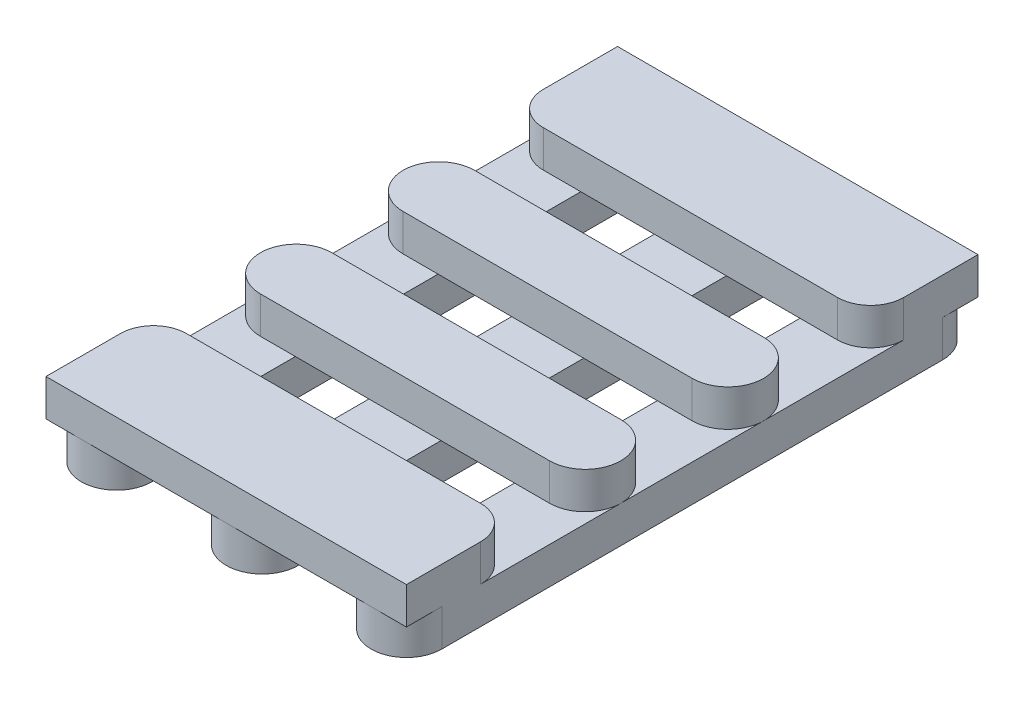
SolidWorks part; units mm, degrees
ref_plane "Front Plane" through (0, 0, 0) normal (0, 0, 1) x (1, 0, 0)
ref_plane "Top Plane" through (0, 0, 0) normal (0, 1, 0) x (1, 0, 0)
ref_plane "Right Plane" through (0, 0, 0) normal (1, 0, 0) x (0, 0, -1)
sketch "Sketch1" plane through (0, 0, 0) normal (0, 1, 0) x (1, 0, 0)
  line L1 (-23.3656, -38.85) -> (16.6344, -38.85)
  line L2 (-27.8656, -34.35) -> (-27.8656, 34.35)
  line L3 (-23.3656, 38.85) -> (16.6344, 38.85)
  line L4 (21.1344, -34.35) -> (21.1344, 34.35)
  arc A0 (-27.8656, -34.35) -> (-23.3656, -38.85) centre (-23.3656, -34.35) ccw
  arc A1 (21.1344, -34.35) -> (16.6344, -38.85) centre (16.6344, -34.35) cw
  arc A2 (-23.3656, 38.85) -> (-27.8656, 34.35) centre (-23.3656, 34.35) ccw
  arc A3 (21.1344, 34.35) -> (16.6344, 38.85) centre (16.6344, 34.35) ccw
  point P0 (0, 0)
  point P14 (21.1344, -38.85)
  point P17 (-27.8656, 38.85)
  point P20 (21.1344, 38.85)
  dimension "D5" = 4.5
  dimension "D1" = 77.7
  dimension "D2" = 49
extrude "Boss-Extrude1" add sketch "Sketch1" along normal blind 10 contours L2 A0 L1 A1 L4 A3 L3 A2
sketch "Sketch2" plane through (0, 10, 0) normal (0, 1, 0) x (1, 0, 0)
  line L0 (-23.3656, 24.25) -> (16.6344, 24.25)
  line L1 (-27.8656, 14.55) -> (21.1344, 14.55)
  line L2 (-27.8656, 4.85) -> (21.1344, 4.85)
  line L3 (-27.8656, -4.85) -> (21.1344, -4.85)
  line L4 (-27.8656, 34.35) -> (-27.8656, -34.35)
  line L5 (-23.3656, -38.85) -> (16.6344, -38.85)
  line L6 (21.1344, -34.35) -> (21.1344, 34.35)
  line L7 (16.6344, 38.85) -> (-23.3656, 38.85)
  line L8 (-27.8656, 34.35) -> (-27.8656, 28.75)
  line L9 (-23.3656, -38.85) -> (16.6344, -38.85)
  line L10 (21.1344, 28.75) -> (21.1344, 34.35)
  line L11 (16.6344, 38.85) -> (-23.3656, 38.85)
  line L12 (-27.8656, -14.55) -> (21.1344, -14.55)
  line L13 (21.1344, 14.55) -> (21.1344, 4.85)
  line L14 (-23.3656, -24.25) -> (16.6344, -24.25)
  line L15 (-27.8656, 14.55) -> (-27.8656, 4.85)
  line L16 (-27.8656, -4.85) -> (-27.8656, -14.55)
  line L17 (21.1344, -4.85) -> (21.1344, -14.55)
  line L18 (-27.8656, -28.75) -> (-27.8656, -33.2156)
  line L19 (-27.8656, -34.35) -> (-27.8656, 34.35) construction
  line L20 (21.1344, -28.75) -> (21.1344, -31.0612)
  line L21 (21.1344, -34.35) -> (21.1344, 34.35) construction
  arc A0 (21.1344, 28.75) -> (16.6344, 24.25) centre (16.6344, 28.75) cw
  arc A1 (-27.8656, 28.75) -> (-23.3656, 24.25) centre (-23.3656, 28.75) ccw
  circle A2 centre (16.2844, 9.7) radius 4.85
  circle A3 centre (16.2844, -9.7) radius 4.85
  arc A4 (-23.3656, 38.85) -> (-27.8656, 34.35) centre (-23.3656, 34.35) ccw
  arc A5 (-27.8656, -34.35) -> (-23.3656, -38.85) centre (-23.3656, -34.35) ccw
  arc A6 (16.6344, -38.85) -> (21.1344, -34.35) centre (16.6344, -34.35) ccw
  arc A7 (21.1344, 34.35) -> (16.6344, 38.85) centre (16.6344, 34.35) ccw
  arc A8 (-23.3656, 38.85) -> (-27.8656, 34.35) centre (-23.3656, 34.35) ccw
  arc A9 (-27.8656, -34.35) -> (-23.3656, -38.85) centre (-23.3656, -34.35) ccw
  arc A10 (16.6344, -38.85) -> (21.1344, -34.35) centre (16.6344, -34.35) ccw
  arc A11 (21.1344, 34.35) -> (16.6344, 38.85) centre (16.6344, 34.35) ccw
  circle A12 centre (-23.0156, 9.7) radius 4.85
  circle A13 centre (-23.0156, -9.7) radius 4.85
  arc A14 (16.6344, -24.25) -> (21.1344, -28.75) centre (16.6344, -28.75) cw
  arc A15 (-23.3656, -24.25) -> (-27.8656, -28.75) centre (-23.3656, -28.75) ccw
  point P28 (16.2844, 14.55)
  point P30 (17.6053, -4.85)
  point P31 (17.6053, -14.55)
  point P32 (-24.5992, -14.55)
  point P33 (-24.5992, -4.85)
  point P34 (-24.5992, 4.85)
  point P35 (-24.5992, 14.55)
  point P48 (21.1344, -24.25)
  point P54 (-27.8656, -24.25)
  line M16 (-27.8656, 34.35) -> (-27.8656, -34.35)
  line M20 (21.1344, -34.35) -> (21.1344, 34.35)
  dimension "D8" = 4.5
  dimension "D9" = 4.5
  dimension "D12" = 9.7
  dimension "D13" = 4.85
  dimension "D15" = 9.7
  dimension "D16" = 9.7
  dimension "D21" = 9.7
  dimension "D22" = 4.5
  dimension "D2" = 14.6
  dimension "D3" = 9.7
  dimension "D4" = 9.7
  dimension "D5" = 14.6
  dimension "D6" = 9.7
  dimension "D7" = 9.7
  dimension "D10" = 4.85
  dimension "D11" = 4.85
  dimension "D14" = 4.85
  dimension "D17" = 4.85
  dimension "D18" = 4.85
  dimension "D19" = 4.85
  dimension "D20" = 4.85
  dimension "D1" = 0
extrude "Cut-Extrude3" cut sketch "Sketch2" against normal blind 5 contours A15 L14 A14 L12 M20 M16 | A13 L16 L12 | A3 L12 M20 | A3 L17 L3 | A13 L3 M16 | L3 L2 M16 M20 | A12 L15 L2 | A2 L2 M20 | A12 L1 M16 | A1 L1 A0 L0 M16 M20 | A2 L13 L1
sketch "Sketch4" plane through (0, 0, 0) normal (0, -1, 0) x (1, 0, 0)
  line L0 (-18.1156, 38.85) -> (-18.1156, -38.85)
  line L1 (-8.2906, 38.85) -> (-8.2906, -38.85)
  line L2 (1.5594, 38.85) -> (1.5594, -38.85)
  line L3 (11.3844, 38.85) -> (11.3844, -38.85)
  line L4 (-23.3656, -38.85) -> (16.6344, -38.85)
  line L5 (21.1344, -34.35) -> (21.1344, 34.35)
  line L6 (16.6344, 38.85) -> (-23.3656, 38.85)
  line L7 (-27.8656, 34.35) -> (-27.8656, -34.35)
  line L8 (-23.3656, -38.85) -> (16.6344, -38.85)
  line L9 (21.1344, -34.35) -> (21.1344, 34.35)
  line L10 (16.6344, 38.85) -> (-23.3656, 38.85)
  line L11 (-27.8656, 34.35) -> (-27.8656, -34.35)
  line L12 (-27.8656, 34.1766) -> (-27.8656, 38.85)
  line L13 (-27.8656, 38.85) -> (-23.3656, 38.85)
  line L14 (-23.3656, 38.85) -> (-23.3656, 35.6156)
  line L15 (-23.3656, 35.6156) -> (-27.8656, 34.1766)
  line L16 (-27.8656, -34.35) -> (-27.8656, -38.85)
  line L17 (-27.8656, -38.85) -> (-23.3656, -38.85)
  line L18 (-23.1567, -35.5858) -> (-27.8656, -34.35)
  line L19 (-23.3656, -38.85) -> (-23.1567, -35.5858)
  line L20 (16.6344, -38.85) -> (21.1344, -38.85)
  line L21 (21.1344, -38.85) -> (21.1344, -34.35)
  line L22 (16.6344, -38.85) -> (16.6344, -34.745)
  line L23 (16.6344, -34.745) -> (21.1344, -34.35)
  line L24 (16.6344, 38.85) -> (21.1344, 38.85)
  line L25 (21.1344, 38.85) -> (21.1344, 34.35)
  line L26 (21.1344, 34.35) -> (17.4288, 36.8474)
  line L27 (17.4288, 36.8474) -> (16.6344, 38.85)
  arc A4 (-27.8656, -34.35) -> (-23.3656, -38.85) centre (-23.3656, -34.35) ccw
  arc A5 (16.6344, -38.85) -> (21.1344, -34.35) centre (16.6344, -34.35) ccw
  arc A6 (21.1344, 34.35) -> (16.6344, 38.85) centre (16.6344, 34.35) ccw
  arc A7 (-23.3656, 38.85) -> (-27.8656, 34.35) centre (-23.3656, 34.35) ccw
  arc A8 (-27.8656, -34.35) -> (-23.3656, -38.85) centre (-23.3656, -34.35) ccw
  arc A9 (16.6344, -38.85) -> (21.1344, -34.35) centre (16.6344, -34.35) ccw
  arc A10 (21.1344, 34.35) -> (16.6344, 38.85) centre (16.6344, 34.35) ccw
  arc A11 (-23.3656, 38.85) -> (-27.8656, 34.35) centre (-23.3656, 34.35) ccw
  arc M21 (-27.8656, -34.35) -> (-23.3656, -38.85) centre (-23.3656, -34.35) ccw
  arc M23 (16.6344, -38.85) -> (21.1344, -34.35) centre (16.6344, -34.35) ccw
  arc M25 (21.1344, 34.35) -> (16.6344, 38.85) centre (16.6344, 34.35) ccw
  arc M27 (-23.3656, 38.85) -> (-27.8656, 34.35) centre (-23.3656, 34.35) ccw
  line M28 (-27.8656, 34.35) -> (-27.8656, -34.35)
  dimension "D3" = 9.75
  dimension "D2" = 9.75
  dimension "D4" = 9.85
  dimension "D5" = 9.825
  dimension "D1" = 0
extrude "Boss-Extrude6" add sketch "Sketch4" along normal blind 5 and the other way blind 10 contours L13 L12 M27 | L15 L14 M27 M28 | L27 L26 M25 | L25 L24 M25 | L23 L22 M23 | L20 L21 M23 | L19 L18 M21 | L16 L17 M21
sketch "Sketch5" plane through (21.1344, 0, 0) normal (1, 0, 0) x (0, 0, -1)
  line L1 (-38.85, 0) -> (41.5848, 0)
  line L2 (-38.85, 0) -> (-38.85, -11.4679)
  line L3 (-38.85, -11.4679) -> (41.5848, -11.4679)
  line L4 (41.5848, 0) -> (41.5848, -11.4679)
  line L14 (9.7, 5) -> (-9.7, 5)
  line L15 (-9.7, 5) -> (-28.75, 5)
  line L16 (-28.75, 5) -> (-28.75, 10)
  line L17 (-28.75, 10) -> (-38.85, 10)
  line L18 (-38.85, 10) -> (-38.85, -5)
  line L19 (-38.85, -5) -> (-34.35, -5)
  line L20 (-34.35, -5) -> (-34.35, 0)
  line L21 (-34.35, 0) -> (34.35, 0)
  line L22 (34.35, 0) -> (34.35, -5)
  line L23 (34.35, -5) -> (38.85, -5)
  line L24 (38.85, -5) -> (38.85, 10)
  line L25 (38.85, 10) -> (28.75, 10)
  line L26 (28.75, 10) -> (28.75, 5)
  line L27 (28.75, 5) -> (9.7, 5)
  line L28 (9.7, 5) -> (-9.7, 5)
  line L29 (-9.7, 5) -> (-28.75, 5)
  line L30 (-28.75, 5) -> (-28.75, 10)
  line L31 (-28.75, 10) -> (-38.85, 10)
  line L32 (-38.85, 10) -> (-38.85, -5)
  line L33 (-38.85, -5) -> (-34.35, -5)
  line L34 (-34.35, -5) -> (-34.35, 0)
  line L35 (-34.35, 0) -> (34.35, 0)
  line L36 (34.35, 0) -> (34.35, -5)
  line L37 (34.35, -5) -> (38.85, -5)
  line L38 (38.85, -5) -> (38.85, 10)
  line L39 (38.85, 10) -> (28.75, 10)
  line L40 (28.75, 10) -> (28.75, 5)
  line L41 (28.75, 5) -> (9.7, 5)
  line M23 (-38.85, 10) -> (-38.85, -5)
  line M24 (-38.85, -5) -> (-34.35, -5)
  line M25 (-34.35, -5) -> (-34.35, 0)
  line M26 (-34.35, 0) -> (34.35, 0)
  line M27 (34.35, 0) -> (34.35, -5)
  line M28 (34.35, -5) -> (38.85, -5)
  line M29 (38.85, -5) -> (38.85, 10)
  dimension "D1" = 0
extrude "Cut-Extrude5" cut sketch "Sketch5" against normal blind 60 contours L4 L1 L2 L3 M29 M28 M27 M26 M25 M24 | L1 M27 M28 M29 | L1 M23 M24 M25
sketch "Sketch6" plane through (0, 0, 0) normal (0, -1, 0) x (1, 0, 0)
  line L0 (-18.2656, 38.85) -> (-18.2656, -38.85)
  line L1 (-8.2656, 38.85) -> (-8.2656, -38.85)
  line L2 (1.5344, 38.85) -> (1.5344, -38.85)
  line L3 (11.5344, 38.85) -> (11.5344, -38.85)
  line L4 (21.1344, 38.85) -> (-27.8656, 38.85)
  line L5 (-27.8656, 38.85) -> (-27.8656, -38.85)
  line L6 (-27.8656, -38.85) -> (21.1344, -38.85)
  line L7 (21.1344, -38.85) -> (21.1344, 38.85)
  line L8 (21.1344, 38.85) -> (-27.8656, 38.85)
  line L9 (-27.8656, 38.85) -> (-27.8656, -38.85)
  line L10 (-27.8656, -38.85) -> (21.1344, -38.85)
  line L11 (21.1344, -38.85) -> (21.1344, 38.85)
  circle A0 centre (-23.0656, 34.05) radius 4.8
  circle A1 centre (-23.0656, -34.05) radius 4.8
  circle A2 centre (16.3344, -34.05) radius 4.8
  circle A3 centre (16.3344, 34.05) radius 4.8
  circle A4 centre (-3.3656, 33.95) radius 4.9
  circle A5 centre (-3.3656, -33.95) radius 4.9
  line M15 (21.1344, 38.85) -> (-27.8656, 38.85)
  line M16 (-27.8656, 38.85) -> (-27.8656, -38.85)
  line M17 (-27.8656, -38.85) -> (21.1344, -38.85)
  line M18 (21.1344, -38.85) -> (21.1344, 38.85)
  dimension "D2" = 9.6
  dimension "D3" = 9.6
  dimension "D4" = 10
  dimension "D5" = 10
  dimension "D1" = 0
extrude "Cut-Extrude7" cut sketch "Sketch6" against normal blind 5 contours A0 L8 M16 | A0 L0 M15 | L1 L0 M15 M17 | A4 L8 L1 | A4 L2 M15 | L3 L2 M15 M17 | A3 L8 L3 | A3 M18 M15 | A2 L10 M18 | A2 L3 M17 | A5 L10 L2 | A5 L1 M17 | A1 L10 L0 | A1 M16 M17
